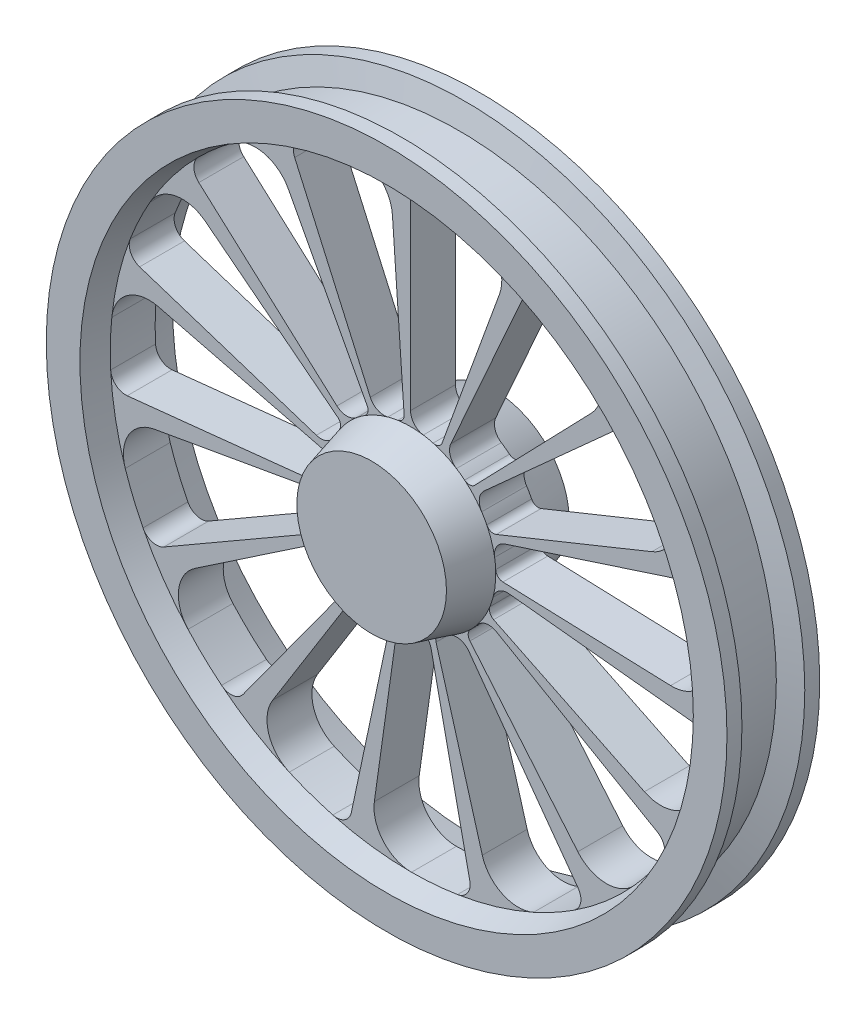
SolidWorks part; units mm, degrees
material "1060 Alloy"
ref_plane "Front Plane" through (0, 0, 0) normal (0, 0, 1) x (1, 0, 0)
ref_plane "Top Plane" through (0, 0, 0) normal (0, 1, 0) x (1, 0, 0)
ref_plane "Right Plane" through (0, 0, 0) normal (1, 0, 0) x (0, 0, -1)
sketch "Sketch1" plane through (0, 0, 0) normal (1, 0, 0) x (0, 0, -1)
  line L0 (0, 0) -> (0, 323.624) construction
  line L1 (-82, 0) -> (82, 0)
  line L2 (82, 0) -> (82, 100)
  line L3 (-82, 0) -> (-82, 100)
  line L4 (82, 100) -> (30, 113.9334)
  line L5 (-82, 100) -> (-30, 113.9334)
  line L6 (30, 113.9334) -> (30, 401.4256)
  line L7 (-30, 113.9334) -> (-30, 401.4256)
  line L8 (30, 401.4256) -> (62, 410)
  line L9 (-30, 401.4256) -> (-62, 410)
  line L10 (62, 410) -> (62, 455)
  line L11 (-62, 410) -> (-62, 455)
  line L12 (62, 455) -> (42, 455)
  line L13 (-62, 455) -> (-42, 455)
  line L14 (42, 455) -> (33.9615, 425)
  line L15 (-42, 455) -> (-33.9615, 425)
  line L16 (33.9615, 425) -> (-33.9615, 425)
  point P19 (0, 425)
  point P20 (0, 0)
  point P21 (0, 0)
  point P22 (-33.9615, 425)
  dimension "D1" = 60
  dimension "D2" = 100
  dimension "D3" = 15
  dimension "D4" = 164
  dimension "D5" = 30
  dimension "D6" = 75
  dimension "D7" = 20
  dimension "D8" = 15
  dimension "D9" = 45
  dimension "D10" = 124
  dimension "D11" = 455
sketch "Sketch2" plane through (0, 0, 0) normal (0, 0, 1) x (1, 0, 0)
  circle A0 centre (0, 0) radius 100
  dimension "D1" = 200
revolve "Revolve2" add sketch "Sketch1" angle 360 about L1
sketch "Sketch3" plane through (0, 0, 30) normal (0, 0, 1) x (1, 0, 0)
  line L0 (0, 132.4317) -> (0, 380.9009)
  line L1 (42.2495, 116.0795) -> (118.9719, 326.8725)
  line L2 (0, 0) -> (0, 248.4693) construction
  line L3 (0, 0) -> (76.7224, 210.793)
  circle A0 centre (0, 0) radius 113.9334 construction
  circle A1 centre (0, 0) radius 401.4256 construction
  circle A2 centre (0, 0) radius 401.4256
  arc A3 (21.0487, 400.8734) -> (82.2294, 392.9133) centre (0, 0) cw
  arc A4 (0, 380.9009) -> (21.0487, 400.8734) centre (20, 380.9009) cw
  arc A5 (118.9719, 326.8725) -> (82.2294, 392.9133) centre (71.9872, 343.9736) ccw
  circle A6 centre (0, 0) radius 113.9334
  arc A7 (17.0134, 112.6559) -> (30.2017, 109.8575) centre (0, 0) cw
  arc A8 (0, 132.4317) -> (17.0134, 112.6559) centre (20, 132.4317) ccw
  arc A9 (42.2495, 116.0795) -> (30.2017, 109.8575) centre (32.8526, 119.4997) cw
  point P7 (80.6107, 221.476)
  point P12 (-19.6584, 381.4255)
  circle M4 centre (0, 0) radius 401.4256
  dimension "D2" = 20
  dimension "D3" = 50
  dimension "D4" = 20
  dimension "D5" = 10
  dimension "D1" = 20
extrude "Cut-Extrude1" cut sketch "Sketch3" against normal through all both and the other way through all contours A9 L1 A5 A4 L0 A8 A6 M4
pattern_circular "CirPattern1" count 15 over 360 about axis through (0, 0, 0) along (0, 0, 1) of "Cut-Extrude1"
equation "\"A\"= 124"
equation "\"B\"= 910"
equation "\"D4@Sketch1\"=\"A\"+40"
equation "\"D10@Sketch1\"=\"A\""
equation "\"D11@Sketch1\"=\"B\"/2"
